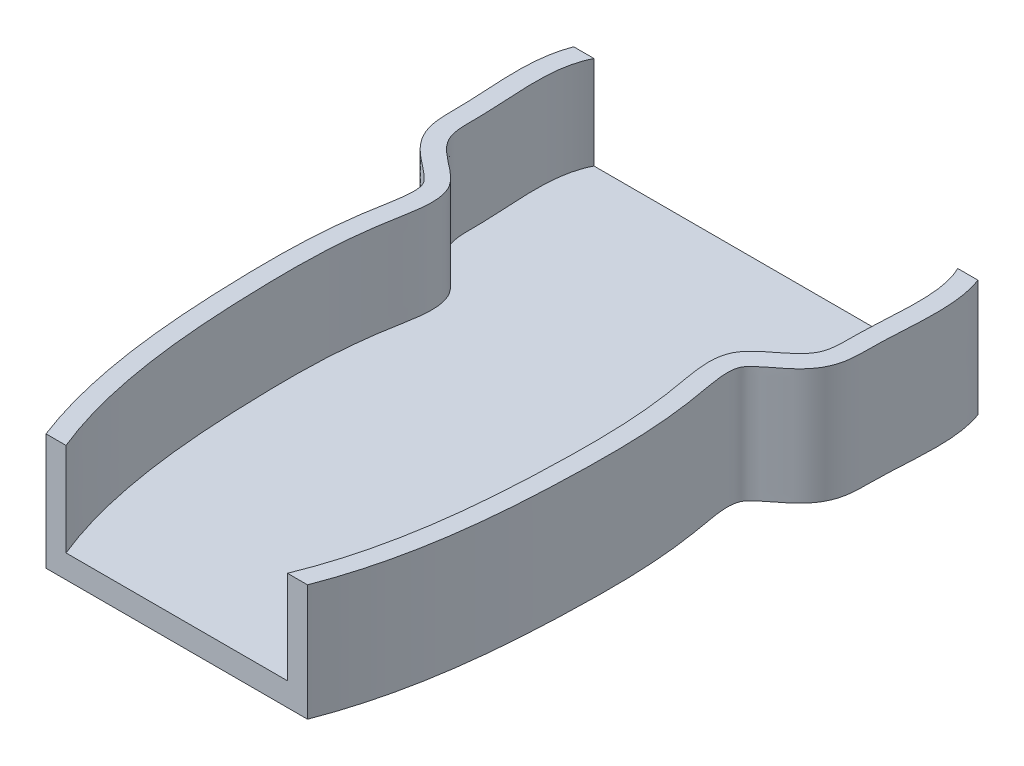
SolidWorks part; units mm, degrees
ref_plane "Front Plane" through (0, 0, 0) normal (0, 0, 1) x (1, 0, 0)
ref_plane "Top Plane" through (0, 0, 0) normal (0, 1, 0) x (1, 0, 0)
ref_plane "Right Plane" through (0, 0, 0) normal (1, 0, 0) x (0, 0, -1)
sketch "Sketch1" plane through (0, 0, 0) normal (0, 1, 0) x (1, 0, 0)
  line L0 (0, 0) -> (0, 27.6542) construction
  line L1 (-21.5265, -3.2766) -> (0, -3.2766)
  line L2 (-13.2207, -92.456) -> (0, -92.456)
  line L3 (-14.7662, -94.996) -> (0, -94.996)
  line L4 (-22.2034, -0.7366) -> (0, -0.7366)
  line L5 (0, -92.456) -> (0, -94.996)
  line L6 (0, -0.7366) -> (0, -3.2766)
  spline S0 degree 3 poles (-21.5265, -3.2766) (-27.673, -6.8029) (-25.3712, -16.3699) (-25.9356, -27.562) (-17.6023, -30.7915) (-20.4875, -42.9961) (-20.7306, -62.4867) (-18.9524, -81.3798) (-13.2207, -92.456) knots 0 0 0 0 0.208498 0.255193 0.340987 0.424768 0.602385 1 1 1 1
  spline S1 degree 1 poles (-22.2034, -0.7366) (-14.7662, -94.996) knots 0 0 1 1 construction
  spline S2 degree 3 poles (-14.7662, -94.996) (-14.9967, -94.5507) (-15.4507, -93.6824) (-16.4134, -91.7674) (-17.8875, -88.4222) (-19.5946, -83.4698) (-21.0525, -77.3976) (-22.0341, -71.2506) (-22.6354, -65.1074) (-22.944, -59.025) (-23.0844, -53.1181) (-23.0022, -48.1367) (-22.6837, -43.9987) (-22.36, -41.3407) (-22.0073, -39.1317) (-21.7049, -37.5006) (-21.4692, -36.0192) (-21.3698, -34.7303) (-21.4466, -33.7311) (-21.6277, -33.1875) (-21.8107, -32.8731) (-22.148, -32.4452) (-22.8673, -31.7792) (-24.0752, -30.8514) (-25.4497, -29.7579) (-26.6047, -28.5832) (-27.4092, -27.3414) (-28.0028, -25.9014) (-28.2504, -24.2439) (-28.2702, -22.4746) (-28.2712, -20.9757) (-28.3387, -19.393) (-28.4289, -17.7671) (-28.552, -15.5523) (-28.6398, -12.7307) (-28.3957, -9.3304) (-27.629, -6.5263) (-26.4755, -4.4088) (-25.5014, -3.1903) (-24.5698, -2.3097) (-23.9246, -1.8025) (-23.3754, -1.4272) (-23.0114, -1.2005) (-22.7257, -1.0362) (-22.5026, -0.9083) (-22.3212, -0.8042) (-22.2034, -0.7366) knots -0.006639 -0.006639 -0.006639 -0.006639 0.009347 0.025332 0.057303 0.121244 0.185186 0.249127 0.313069 0.37701 0.440952 0.504893 0.536864 0.568835 0.58482 0.600805 0.616791 0.632776 0.648762 0.664747 0.67274 0.680732 0.696718 0.712703 0.728688 0.744674 0.752666 0.760659 0.776645 0.79263 0.808615 0.824601 0.840586 0.856571 0.888542 0.920513 0.952484 0.968469 0.984454 0.992447 1.00044 1.004436 1.008432 1.010431 1.012429 1.016425 1.016425 1.016425 1.016425
  point P1 (-23.7363, -5.08)
  point P2 (-13.2207, -92.456)
  point P4 (-25.7302, -21.6408)
  point P6 (-18.7579, -75.438)
  point P7 (-25.2095, -25.9842)
  point P8 (-21.5265, -3.2766)
  point P18 (-19.558, -31.6992)
  point P19 (-19.4945, -39.5478)
  point P20 (-20.4597, -56.1594)
  dimension "D1" = 5.08
  dimension "D2" = 47.4726
  dimension "D3" = 21.6408
  dimension "D4" = 51.4604
  dimension "D5" = 25.9842
  dimension "D6" = 50.419
  dimension "D7" = 31.6992
  dimension "D8" = 39.116
  dimension "D9" = 39.5478
  dimension "D10" = 38.989
  dimension "D11" = 56.1594
  dimension "D12" = 40.9194
  dimension "D13" = 75.438
  dimension "D14" = 37.5158
  dimension "D15" = 92.456
  dimension "D16" = 26.4414
  dimension "D17" = 3.2766
  dimension "D18" = 43.053
  dimension "D19" = 2.54
extrude "Boss-Extrude1" add sketch "Sketch1" along normal blind 12.7
mirror "Mirror1" about plane through (0, 0, 0) normal (1, 0, 0) of "Boss-Extrude1"
sketch "Sketch3" plane through (0, 0, 0) normal (0, 1, 0) x (1, 0, 0)
  line L2 (-14.7662, -94.996) -> (14.7662, -94.996)
  line L3 (22.2034, -0.7366) -> (-22.2034, -0.7366)
  line L4 (-14.7662, -94.996) -> (14.7662, -94.996)
  line L5 (22.2034, -0.7366) -> (-22.2034, -0.7366)
  spline S2 degree 3 poles (-1169.2351, -3915.5543) (8.9305, -84.9479) (3.9194, -116.62) (16.4134, -91.7674) (17.8875, -88.4222) (19.5946, -83.4698) (21.0525, -77.3976) (22.0341, -71.2506) (22.6354, -65.1074) (22.944, -59.025) (23.0844, -53.1181) (23.0022, -48.1367) (22.6837, -43.9987) (22.36, -41.3407) (22.0073, -39.1317) (21.7049, -37.5006) (21.4692, -36.0192) (21.3698, -34.7303) (21.4466, -33.7311) (21.6277, -33.1875) (21.8107, -32.8731) (22.148, -32.4452) (22.8673, -31.7792) (24.0752, -30.8514) (25.4497, -29.7579) (26.6047, -28.5832) (27.4092, -27.3414) (28.0028, -25.9014) (28.2504, -24.2439) (28.2702, -22.4746) (28.2712, -20.9757) (28.3387, -19.393) (28.4289, -17.7671) (28.552, -15.5523) (28.6398, -12.7307) (28.3957, -9.3304) (27.629, -6.5263) (26.4755, -4.4088) (25.5014, -3.1903) (24.5698, -2.3097) (23.9246, -1.8025) (23.3754, -1.4272) (23.0114, -1.2005) (22.7257, -1.0362) (14.5234, 3.6653) (-26.9688, 27.7716) (3476.9923, -2014.7148) knots -0.772508 -0.772508 -0.772508 -0.772508 0.009347 0.025332 0.057303 0.121244 0.185186 0.249127 0.313069 0.37701 0.440952 0.504893 0.536864 0.568835 0.58482 0.600805 0.616791 0.632776 0.648762 0.664747 0.67274 0.680732 0.696718 0.712703 0.728688 0.744674 0.752666 0.760659 0.776645 0.79263 0.808615 0.824601 0.840586 0.856571 0.888542 0.920513 0.952484 0.968469 0.984454 0.992447 1.00044 1.004436 1.008432 1.010431 1.012429 1.302261 1.302261 1.302261 1.302261 only from (14.7662, -94.996) to (22.2034, -0.7366)
  spline S3 degree 3 poles (-3477.4947, -2015.0077) (26.9727, 27.7739) (-14.523, 3.6655) (-22.7257, -1.0362) (-23.0114, -1.2005) (-23.3754, -1.4272) (-23.9246, -1.8025) (-24.5698, -2.3097) (-25.5014, -3.1903) (-26.4755, -4.4088) (-27.629, -6.5263) (-28.3957, -9.3304) (-28.6398, -12.7307) (-28.552, -15.5523) (-28.4289, -17.7671) (-28.3387, -19.393) (-28.2712, -20.9757) (-28.2702, -22.4746) (-28.2504, -24.2439) (-28.0028, -25.9014) (-27.4092, -27.3414) (-26.6047, -28.5832) (-25.4497, -29.7579) (-24.0752, -30.8514) (-22.8673, -31.7792) (-22.148, -32.4452) (-21.8107, -32.8731) (-21.6277, -33.1875) (-21.4466, -33.7311) (-21.3698, -34.7303) (-21.4692, -36.0192) (-21.7049, -37.5006) (-22.0073, -39.1317) (-22.36, -41.3407) (-22.6837, -43.9987) (-23.0022, -48.1367) (-23.0844, -53.1181) (-22.944, -59.025) (-22.6354, -65.1074) (-22.0341, -71.2506) (-21.0525, -77.3976) (-19.5946, -83.4698) (-17.8875, -88.4222) (-16.4134, -91.7674) (-3.9195, -116.6197) (-8.9304, -84.9485) (1169.2019, -3915.4462) knots -0.292488 -0.292488 -0.292488 -0.292488 -0.002642 -0.000644 0.001354 0.005351 0.009347 0.01734 0.025332 0.041318 0.057303 0.089274 0.121244 0.153215 0.169201 0.185186 0.201171 0.217157 0.233142 0.249127 0.25712 0.265113 0.281098 0.297083 0.313069 0.329054 0.337047 0.34504 0.361025 0.37701 0.392996 0.408981 0.424966 0.440952 0.472923 0.504893 0.568835 0.632776 0.696718 0.760659 0.824601 0.888542 0.952484 0.984454 1.00044 1.782287 1.782287 1.782287 1.782287 only from (-22.2034, -0.7366) to (-14.7662, -94.996)
  spline S4 degree 3 poles (14.7662, -94.996) (14.9967, -94.5507) (15.4507, -93.6824) (16.4134, -91.7674) (17.8875, -88.4222) (19.5946, -83.4698) (21.0525, -77.3976) (22.0341, -71.2506) (22.6354, -65.1074) (22.944, -59.025) (23.0844, -53.1181) (23.0022, -48.1367) (22.6837, -43.9987) (22.36, -41.3407) (22.0073, -39.1317) (21.7049, -37.5006) (21.4692, -36.0192) (21.3698, -34.7303) (21.4466, -33.7311) (21.6277, -33.1875) (21.8107, -32.8731) (22.148, -32.4452) (22.8673, -31.7792) (24.0752, -30.8514) (25.4497, -29.7579) (26.6047, -28.5832) (27.4092, -27.3414) (28.0028, -25.9014) (28.2504, -24.2439) (28.2702, -22.4746) (28.2712, -20.9757) (28.3387, -19.393) (28.4289, -17.7671) (28.552, -15.5523) (28.6398, -12.7307) (28.3957, -9.3304) (27.629, -6.5263) (26.4755, -4.4088) (25.5014, -3.1903) (24.5698, -2.3097) (23.9246, -1.8025) (23.3754, -1.4272) (23.0114, -1.2005) (22.7257, -1.0362) (22.5026, -0.9083) (22.3212, -0.8042) (22.2034, -0.7366) knots -0.006639 -0.006639 -0.006639 -0.006639 0.009347 0.025332 0.057303 0.121244 0.185186 0.249127 0.313069 0.37701 0.440952 0.504893 0.536864 0.568835 0.58482 0.600805 0.616791 0.632776 0.648762 0.664747 0.67274 0.680732 0.696718 0.712703 0.728688 0.744674 0.752666 0.760659 0.776645 0.79263 0.808615 0.824601 0.840586 0.856571 0.888542 0.920513 0.952484 0.968469 0.984454 0.992447 1.00044 1.004436 1.008432 1.010431 1.012429 1.016425 1.016425 1.016425 1.016425
  spline S5 degree 3 poles (-22.2034, -0.7366) (-22.3212, -0.8042) (-22.5026, -0.9083) (-22.7257, -1.0362) (-23.0114, -1.2005) (-23.3754, -1.4272) (-23.9246, -1.8025) (-24.5698, -2.3097) (-25.5014, -3.1903) (-26.4755, -4.4088) (-27.629, -6.5263) (-28.3957, -9.3304) (-28.6398, -12.7307) (-28.552, -15.5523) (-28.4289, -17.7671) (-28.3387, -19.393) (-28.2712, -20.9757) (-28.2702, -22.4746) (-28.2504, -24.2439) (-28.0028, -25.9014) (-27.4092, -27.3414) (-26.6047, -28.5832) (-25.4497, -29.7579) (-24.0752, -30.8514) (-22.8673, -31.7792) (-22.148, -32.4452) (-21.8107, -32.8731) (-21.6277, -33.1875) (-21.4466, -33.7311) (-21.3698, -34.7303) (-21.4692, -36.0192) (-21.7049, -37.5006) (-22.0073, -39.1317) (-22.36, -41.3407) (-22.6837, -43.9987) (-23.0022, -48.1367) (-23.0844, -53.1181) (-22.944, -59.025) (-22.6354, -65.1074) (-22.0341, -71.2506) (-21.0525, -77.3976) (-19.5946, -83.4698) (-17.8875, -88.4222) (-16.4134, -91.7674) (-15.4507, -93.6824) (-14.9967, -94.5507) (-14.7662, -94.996) knots -0.006639 -0.006639 -0.006639 -0.006639 -0.002642 -0.000644 0.001354 0.005351 0.009347 0.01734 0.025332 0.041318 0.057303 0.089274 0.121244 0.153215 0.169201 0.185186 0.201171 0.217157 0.233142 0.249127 0.25712 0.265113 0.281098 0.297083 0.313069 0.329054 0.337047 0.34504 0.361025 0.37701 0.392996 0.408981 0.424966 0.440952 0.472923 0.504893 0.568835 0.632776 0.696718 0.760659 0.824601 0.888542 0.952484 0.984454 1.00044 1.016425 1.016425 1.016425 1.016425
  dimension "D1" = 0
extrude "Boss-Extrude2" add sketch "Sketch3" against normal blind 3.175
sketch "Sketch4" plane through (0, 0, 0) normal (0, 1, 0) x (1, 0, 0)
  line L1 (-34.3632, 7.3821) -> (33.0011, 7.3821)
  line L2 (-34.3632, 7.3821) -> (-34.3632, -6.6723)
  line L3 (-34.3632, -6.6723) -> (33.0011, -6.6723)
  line L4 (33.0011, 7.3821) -> (33.0011, -6.6723)
extrude "Cut-Extrude1" cut sketch "Sketch4" against normal through all both and the other way through all
sketch "Sketch5" plane through (0, 0, 0) normal (0, 1, 0) x (1, 0, 0)
  line L1 (-25.9901, -88.3745) -> (23.66, -88.3745)
  line L2 (-25.9901, -88.3745) -> (-25.9901, -99.7274)
  line L3 (-25.9901, -99.7274) -> (23.66, -99.7274)
  line L4 (23.66, -88.3745) -> (23.66, -99.7274)
extrude "Cut-Extrude2" cut sketch "Sketch5" against normal through all both and the other way through all
